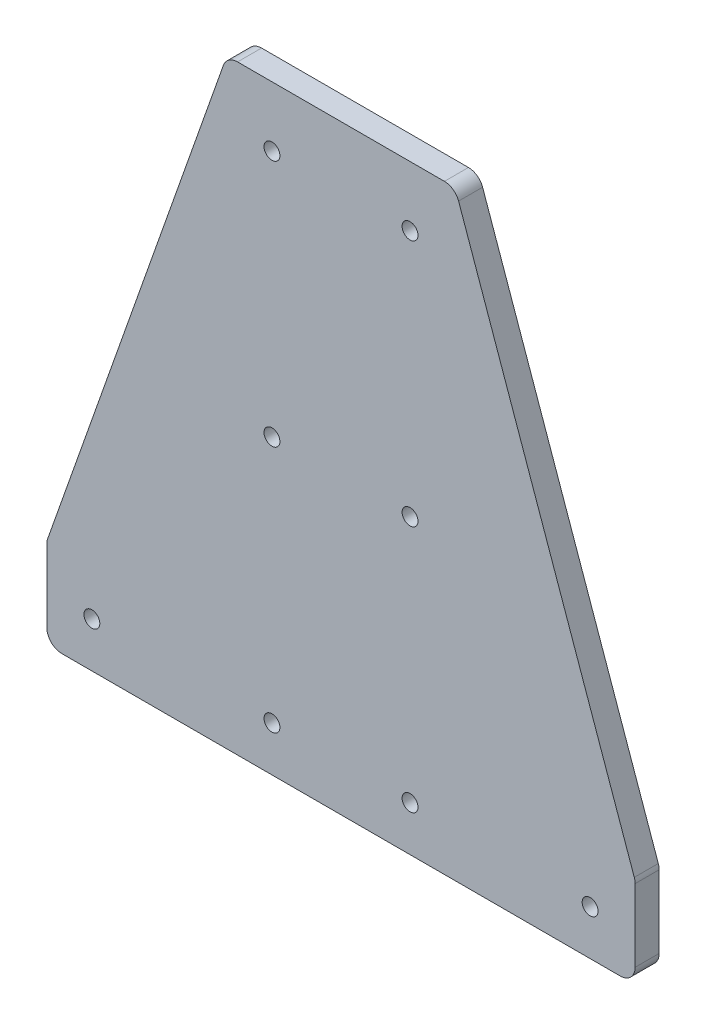
SolidWorks part; units mm, degrees
ref_plane "Front Plane" through (0, 0, 0) normal (0, 0, 1) x (1, 0, 0)
ref_plane "Top Plane" through (0, 0, 0) normal (0, 1, 0) x (1, 0, 0)
ref_plane "Right Plane" through (0, 0, 0) normal (1, 0, 0) x (0, 0, -1)
sketch "Sketch1" plane through (0, 0, 0) normal (0, 0, 1) x (1, 0, 0)
  line L0 (-98, -30) -> (98, -30)
  line L1 (98, -30) -> (98, 0)
  line L2 (98, 0) -> (38, 170)
  line L3 (38, 170) -> (-38, 170)
  line L4 (-38, 170) -> (-98, 0)
  line L5 (-98, 0) -> (-98, -30)
  line L6 (55, 0) -> (-55, 0) construction
  line L7 (0, -55) -> (0, 55) construction
  dimension "D1" = 30
  dimension "D2" = 196
  dimension "D3" = 30
  dimension "D4" = 98
  dimension "D5" = 200
  dimension "D6" = 60
  dimension "D7" = 76
  dimension "D8" = 30
extrude "Boss-Extrude1" add sketch "Sketch1" along normal blind 8
hole_wizard "M5 Clearance Hole1" positions "Sketch4" profile "Sketch3" hole size "M5" standard "ISO" end condition through all
sketch "Sketch4" plane through (0, 0, 8) normal (0, 0, 1) x (1, 0, 0)
  line L0 (0, 0) -> (0, 82.324) construction
  line L1 (0, -55) -> (0, 55) construction
  line L2 (-98, -30) -> (98, -30) construction
  line L4 (-23, -15) -> (-23, 150)
  line L5 (-98, 0) -> (-98, -30) construction
  line L6 (55, 0) -> (-55, 0) construction
  point P0 (-23, 150)
  point P2 (-23, 67.5)
  point P3 (-23, -15)
  point P17 (23, -15)
  point P18 (23, 150)
  point P19 (23, 67.5)
  point P28 (-83, -15)
  point P36 (83, -15)
  dimension "D1" = 180
  dimension "D2" = 15
  dimension "D3" = 23
  dimension "D4" = 15
  dimension "D5" = 15
sketch "Sketch3" plane through (-23, 150, 8) normal (1, 0, 0) x (0, -1, 0)
  line L0 (0, 0) -> (0, 8)
  line L1 (0, 8) -> (2.65, 8)
  line L2 (2.65, 8) -> (2.65, 0)
  line L5 (2.65, 0) -> (0, 0)
  line L11 (0, -6.35) -> (0, 107.95) construction
  dimension "Thru Hole Dia." = 5.3
  dimension "Thru Hole Depth" = 8
fillet "Fillet1" radius 5 6 edges at (38, 170, 4) (98, 0, 4) (98, -30, 4) (-98, -30, 4) (-98, 0, 4) (-38, 170, 4)
